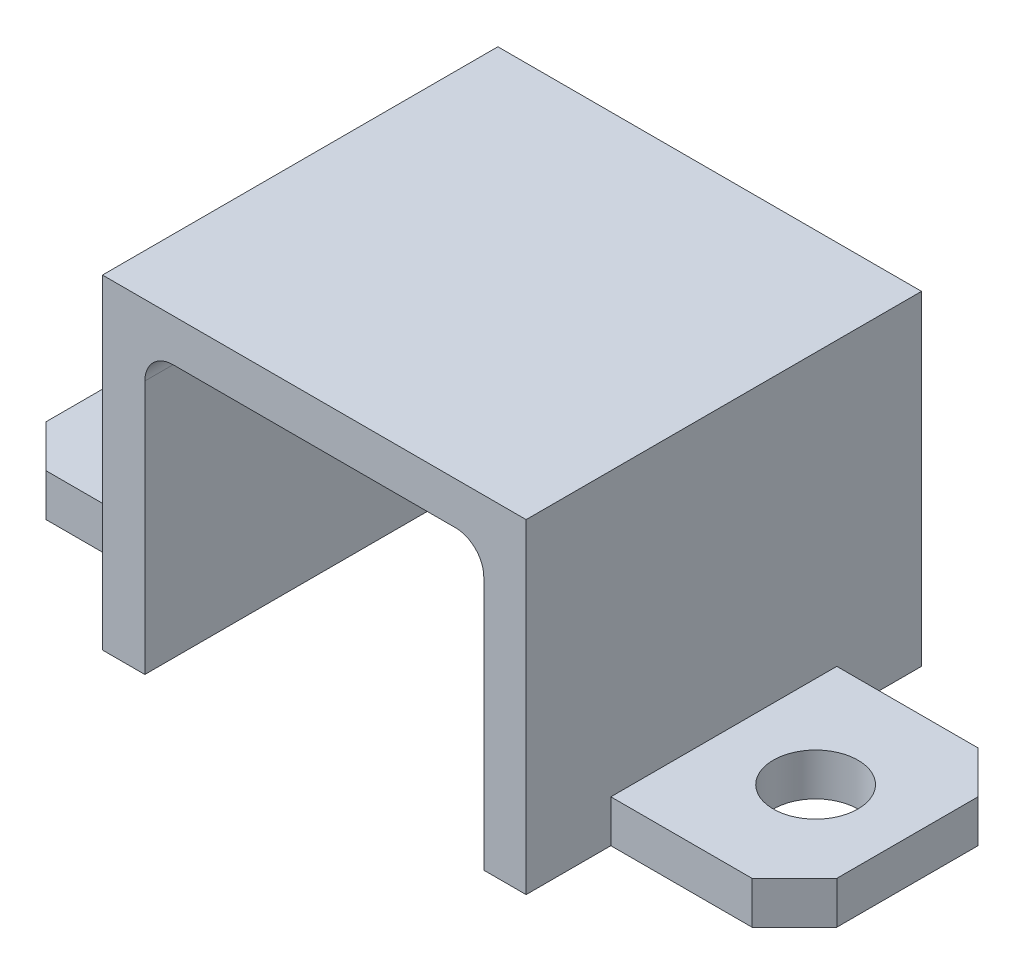
SolidWorks part; units mm, degrees
ref_plane "Front Plane" through (0, 0, 0) normal (0, 0, 1) x (1, 0, 0)
ref_plane "Top Plane" through (0, 0, 0) normal (0, 1, 0) x (1, 0, 0)
ref_plane "Right Plane" through (0, 0, 0) normal (1, 0, 0) x (0, 0, -1)
sketch "Sketch1" plane through (0, 0, 0) normal (0, 0, 1) x (1, 0, 0)
  line L0 (0.5, 1.5) -> (0.5, 11.5)
  line L1 (0.5, 11.5) -> (15.5, 11.5)
  line L2 (15.5, 11.5) -> (15.5, 1.5)
  line L3 (2, 0) -> (2, 9)
  line L4 (3, 10) -> (13, 10)
  line L5 (14, 9) -> (14, 0)
  line L6 (14, 0) -> (22, 0)
  line L7 (22, 0) -> (22, 1.5)
  line L8 (22, 1.5) -> (15.5, 1.5)
  line L9 (2, 0) -> (-6, 0)
  line L10 (-6, 0) -> (-6, 1.5)
  line L11 (-6, 1.5) -> (0.5, 1.5)
  arc A0 (13, 10) -> (14, 9) centre (13, 9) cw
  arc A1 (2, 9) -> (3, 10) centre (3, 9) cw
  point P10 (14, 10)
  point P18 (2, 10)
  dimension "D1" = 1
  dimension "D2" = 15
  dimension "D3" = 1.5
  dimension "D4" = 10
  dimension "D5" = 10
  dimension "D6" = 1.5
  dimension "D7" = 1.5
  dimension "D8" = 6.5
  dimension "D9" = 6.5
  dimension "D10" = 1.5
extrude "Boss-Extrude1" add sketch "Sketch1" along normal blind 11
sketch "Sketch3" plane through (0, 0, 11) normal (0, 0, 1) x (1, 0, 0)
  line L1 (0.5, 1.5) -> (-6, 1.5)
  line L2 (0.5, 1.5) -> (0.5, 0)
  line L3 (0.5, 0) -> (-6, 0)
  line L4 (-6, 1.5) -> (-6, 0)
  line L5 (15.5, 1.5) -> (22, 1.5)
  line L6 (15.5, 1.5) -> (15.5, 0)
  line L7 (15.5, 0) -> (22, 0)
  line L8 (22, 1.5) -> (22, 0)
extrude "Cut-Extrude5" cut sketch "Sketch3" against normal blind 3
sketch "Sketch6" plane through (0, 1.5, 0) normal (0, 1, 0) x (1, 0, 0)
  line L0 (8, 0) -> (8, -1.6612) construction
  line L1 (15.5, 0) -> (0.5, 0) construction
  line L2 (-6, -1.5) -> (-4.5, 0)
  line L3 (-6, -8) -> (-6, 0) construction
  line L4 (0.5, 0) -> (-6, 0) construction
  line L5 (-4.5, 0) -> (-6, 0)
  line L6 (-6, 0) -> (-6, -1.5)
  line L7 (-6, -4) -> (3.2683, -4) construction
  line L8 (20.5, 0) -> (22, 0)
  line L9 (22, -1.5) -> (20.5, 0)
  line L10 (22, 0) -> (22, -1.5)
  line L11 (22, -6.5) -> (20.5, -8)
  line L12 (22, -8) -> (22, -6.5)
  line L13 (20.5, -8) -> (22, -8)
  line L14 (-4.5, -8) -> (-6, -8)
  line L15 (-6, -6.5) -> (-4.5, -8)
  line L16 (-6, -8) -> (-6, -6.5)
  circle A0 centre (-2.75, -4) radius 1.5
  circle A1 centre (18.75, -4) radius 1.5
  circle A2 centre (-2.75, -4) radius 2.65 construction
  circle A3 centre (18.75, -4) radius 2.65 construction
  dimension "D1" = 3
  dimension "D2" = 5.3
  dimension "D3" = 5.3
  dimension "D4" = 1.5
  dimension "D5" = 1.5
extrude "Cut-Extrude7" cut sketch "Sketch6" against normal through all
sketch "草图1" plane through (0, 0, 0) normal (0, 0, -1) x (-1, 0, 0)
  line L0 (-0.5, 1.5) -> (-0.5, 0)
  line L1 (-15.5, 1.5) -> (-15.5, 0)
  line L12 (4.5, 0) -> (4.5, 1.5)
  line L13 (4.5, 1.5) -> (-0.5, 1.5)
  line L14 (-0.5, 1.5) -> (-0.5, 11.5)
  line L15 (-0.5, 11.5) -> (-15.5, 11.5)
  line L16 (-15.5, 11.5) -> (-15.5, 1.5)
  line L17 (-15.5, 1.5) -> (-20.5, 1.5)
  line L18 (-20.5, 1.5) -> (-20.5, 0)
  line L19 (-20.5, 0) -> (-14, 0)
  line L20 (-14, 0) -> (-14, 9)
  line L21 (-13, 10) -> (-3, 10)
  line L22 (-2, 9) -> (-2, 0)
  line L23 (-2, 0) -> (4.5, 0)
  line L26 (-0.5, 1.5) -> (-0.5, 11.5)
  line L27 (-0.5, 11.5) -> (-15.5, 11.5)
  line L28 (-15.5, 11.5) -> (-15.5, 1.5)
  line L31 (-15.5, 0) -> (-14, 0)
  line L32 (-14, 0) -> (-14, 9)
  line L33 (-13, 10) -> (-3, 10)
  line L34 (-2, 9) -> (-2, 0)
  line L35 (-2, 0) -> (-0.5, 0)
  arc A2 (-13, 10) -> (-14, 9) centre (-13, 9) ccw
  arc A3 (-2, 9) -> (-3, 10) centre (-3, 9) ccw
  arc A4 (-13, 10) -> (-14, 9) centre (-13, 9) ccw
  arc A5 (-2, 9) -> (-3, 10) centre (-3, 9) ccw
  dimension "D1" = 0
extrude "凸台-拉伸1" add sketch "草图1" along normal blind 3
